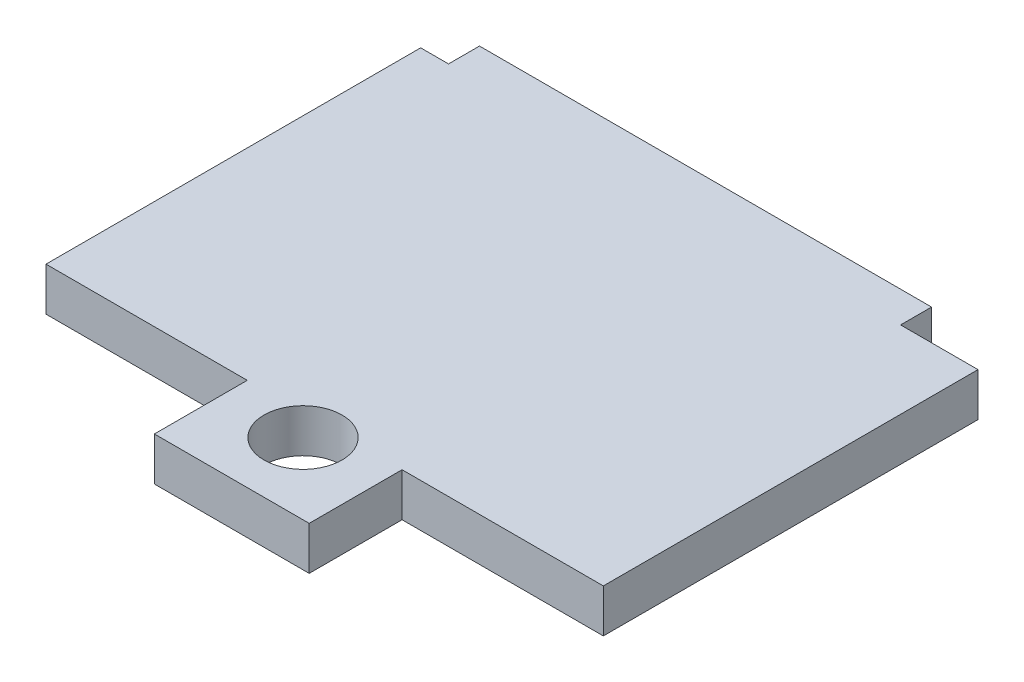
SolidWorks part; units mm, degrees
ref_plane "Front Plane" through (0, 0, 0) normal (0, 0, 1) x (1, 0, 0)
ref_plane "Top Plane" through (0, 0, 0) normal (0, 1, 0) x (1, 0, 0)
ref_plane "Right Plane" through (0, 0, 0) normal (1, 0, 0) x (0, 0, -1)
sketch "Sketch1" plane through (0, 0, 0) normal (0, 1, 0) x (1, 0, 0)
  line L0 (0, 15.367) -> (0, 0)
  line L1 (0, 0) -> (8.255, 0)
  line L2 (8.255, 0) -> (8.255, -3.81)
  line L3 (8.255, -3.81) -> (14.605, -3.81)
  line L4 (14.605, -3.81) -> (14.605, 0)
  line L5 (14.605, 0) -> (22.86, 0)
  line L6 (22.86, 0) -> (22.86, 15.367)
  line L8 (0, 15.367) -> (1.143, 15.367)
  line L9 (1.143, 15.367) -> (1.143, 16.637)
  line L10 (1.143, 16.637) -> (19.685, 16.637)
  line L11 (19.685, 16.637) -> (19.685, 15.367)
  line L12 (19.685, 15.367) -> (22.86, 15.367)
  dimension "D1" = 18.542
  dimension "D2" = 22.86
  dimension "D3" = 1.143
  dimension "D4" = 15.367
  dimension "D5" = 1.27
  dimension "D6" = 3.81
  dimension "D7" = 6.35
  dimension "D8" = 8.255
extrude "Boss-Extrude1" add sketch "Sketch1" along normal blind 1.778
hole_wizard "M3 Clearance Hole1" positions "Sketch2" profile "Sketch3" hole size "M3" standard "ANSI Metric" end condition through all
sketch "Sketch2" plane through (0, 1.778, 0) normal (0, 1, 0) x (1, 0, 0)
  line L0 (8.255, -3.81) -> (14.605, -3.81) construction
  line L1 (23.2514, 2.0338) -> (23.2514, -3.81) construction
  line L2 (12.3825, 2.0338) -> (23.495, 2.0338) construction
  point P0 (11.43, -0.8881)
  point P5 (11.43, -3.81)
  point P13 (23.2514, -0.8881)
sketch "Sketch3" plane through (11.43, 1.778, 0.8881) normal (1, 0, 0) x (0, 0, 1)
  line L0 (0, 0) -> (0, 1.778)
  line L1 (0, 1.778) -> (1.6, 1.778)
  line L2 (1.6, 1.778) -> (1.6, 0)
  line L5 (1.6, 0) -> (0, 0)
  line L11 (0, -6.35) -> (0, 107.95) construction
  dimension "Thru Hole Dia." = 3.2
  dimension "Thru Hole Depth" = 1.778
sketch "Sketch4" plane through (0, 0, 0) normal (0, -1, 0) x (1, 0, 0)
  line L1 (15.24, -4.3028) -> (17.78, -4.3028)
  line L2 (15.24, -4.3028) -> (15.24, -13.4468)
  line L3 (15.24, -13.4468) -> (17.78, -13.4468)
  line L4 (17.78, -4.3028) -> (17.78, -13.4468)
  line L5 (0, -4.3028) -> (2.54, -4.3028)
  line L6 (0, -4.3028) -> (0, -13.4468)
  line L7 (0, -13.4468) -> (2.54, -13.4468)
  line L8 (2.54, -4.3028) -> (2.54, -13.4468)
  line L9 (22.86, 0) -> (22.86, -15.367) construction
  line L10 (-0.635, -12.8914) -> (23.495, -12.8914) construction
  dimension "D1" = 9.144
  dimension "D2" = 2.54
  dimension "D3" = 12.7
  dimension "D4" = 5.08
  dimension "D5" = 0.5554
extrude "Boss-Extrude2" add sketch "Sketch4" along normal blind 1.397
sketch "Sketch6" plane through (0, 0, 0) normal (0, -1, 0) x (1, 0, 0)
  text T0 "<b>55</b>"
  point P1 (6.3907, -9.1548)
  point P2 (5.7347, -10.2412)
  point P3 (6.5413, -10.0061)
  point P4 (0, 0)
extrude "Cut-Extrude2" cut sketch "Sketch6" against normal blind 0.508
